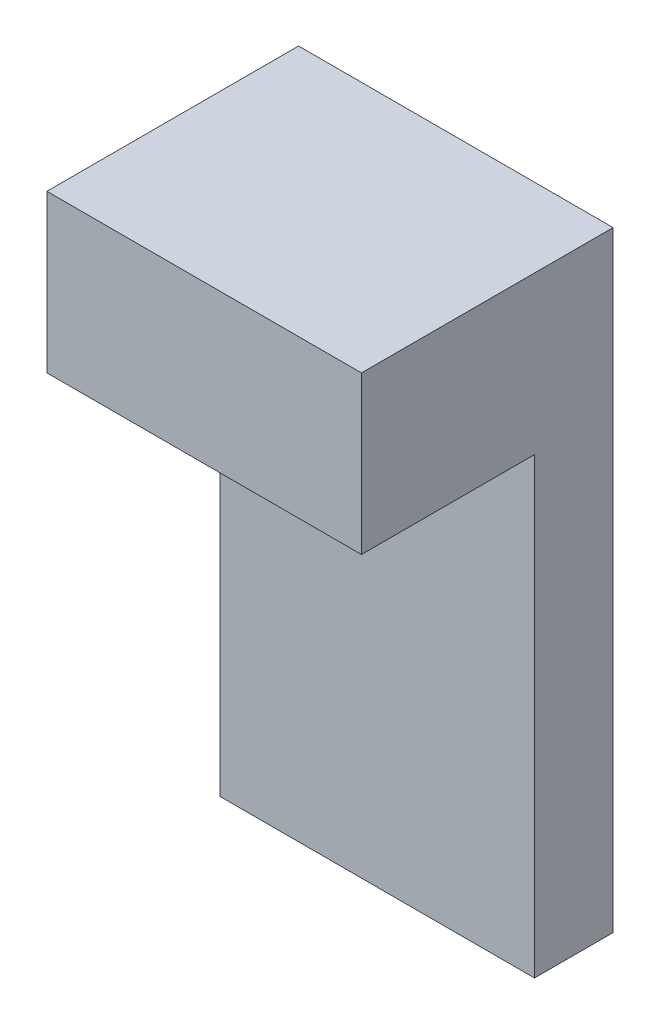
SolidWorks part; units mm, degrees
ref_plane "Front Plane" through (0, 0, 0) normal (0, 0, 1) x (1, 0, 0)
ref_plane "Top Plane" through (0, 0, 0) normal (0, 1, 0) x (1, 0, 0)
ref_plane "Right Plane" through (0, 0, 0) normal (1, 0, 0) x (0, 0, -1)
sketch "Sketch1" plane through (0, 0, 0) normal (0, 0, 1) x (1, 0, 0)
  line L1 (-15.6192, 31.9406) -> (-2.9192, 31.9406)
  line L2 (-15.6192, 31.9406) -> (-15.6192, -17.3594)
  line L3 (-15.6192, -17.3594) -> (-2.9192, -17.3594)
  line L4 (-2.9192, 31.9406) -> (-2.9192, -17.3594)
  line L5 (-15.6192, 31.9406) -> (-2.9192, -17.3594) construction
  line L6 (-15.6192, -17.3594) -> (-2.9192, 31.9406) construction
  line L7 (15.2808, -17.3594) -> (-33.8192, -17.3594) construction
  point P0 (-9.2692, 7.2906)
  dimension "D1" = 12.7
  dimension "D2" = 49.3
extrude "Boss-Extrude1" add sketch "Sketch1" along normal blind 6.35
sketch "Sketch3" plane through (-15.6192, 0, 0) normal (-1, 0, 0) x (0, 0, 1)
  line L0 (0, 31.9406) -> (0, -17.3594) construction
  line L1 (6.35, -17.3594) -> (0, -17.3594)
  line L2 (6.35, -17.3594) -> (6.35, 31.9406)
  line L3 (6.35, 31.9406) -> (0, 31.9406)
  line L4 (0, -17.3594) -> (0, 31.9406)
  line L6 (6.35, 31.9406) -> (0, 31.9406) construction
extrude "Boss-Extrude3" add sketch "Sketch3" along normal blind 12.7
sketch "Sketch2" plane through (0, 0, 6.35) normal (0, 0, 1) x (1, 0, 0)
  line L1 (-2.9192, 19.2406) -> (-28.3192, 19.2406)
  line L2 (-2.9192, 19.2406) -> (-2.9192, 31.9406)
  line L3 (-2.9192, 31.9406) -> (-28.3192, 31.9406)
  line L4 (-28.3192, 19.2406) -> (-28.3192, 31.9406)
  line L5 (-2.9192, 19.2406) -> (-28.3192, 31.9406) construction
  line L6 (-2.9192, 31.9406) -> (-28.3192, 19.2406) construction
  line L7 (-2.9192, -17.3594) -> (-2.9192, 31.9406) construction
  line L8 (-2.9192, 31.9406) -> (-28.3192, 31.9406) construction
  line L9 (-28.3192, -17.3594) -> (-28.3192, 31.9406) construction
  point P5 (-9.2692, 10.7014)
  point P12 (0, 0)
  dimension "D1" = 12.7
extrude "Boss-Extrude2" add sketch "Sketch2" along normal blind 13.97
